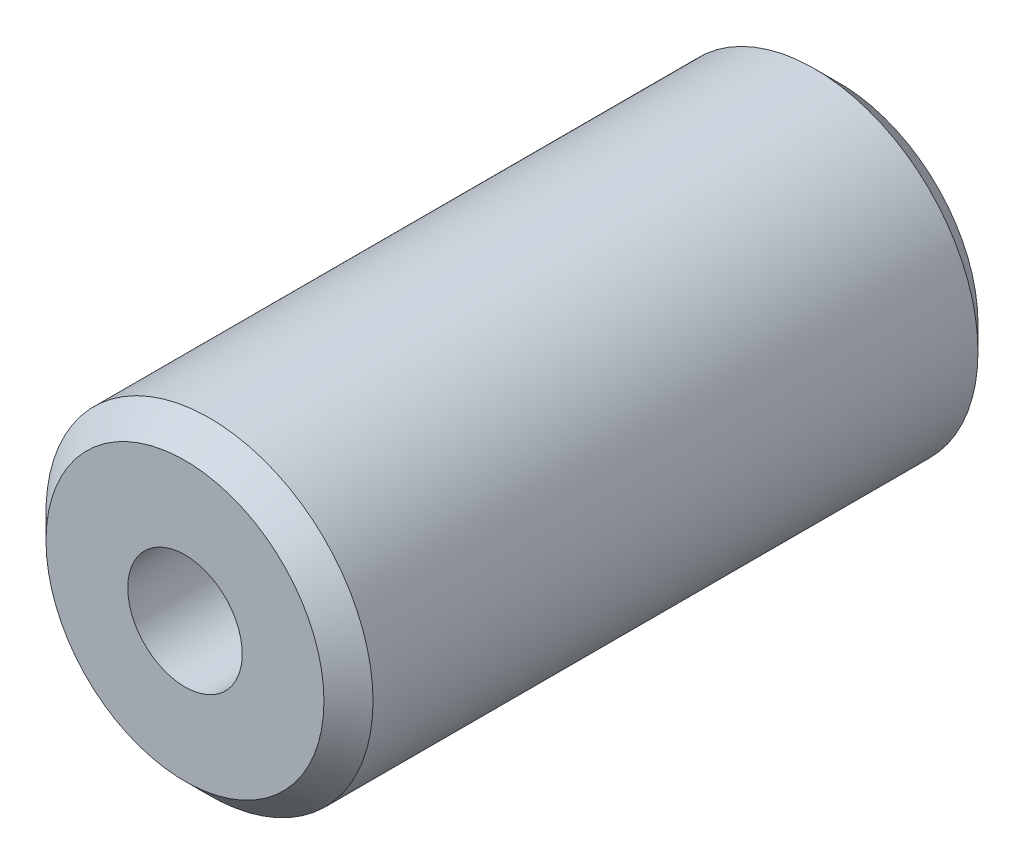
SolidWorks part; units mm, degrees
ref_plane "Front Plane" through (0, 0, 0) normal (0, 0, 1) x (1, 0, 0)
ref_plane "Top Plane" through (0, 0, 0) normal (0, 1, 0) x (1, 0, 0)
ref_plane "Right Plane" through (0, 0, 0) normal (1, 0, 0) x (0, 0, -1)
sketch "Sketch1" plane through (0, 0, 0) normal (0, 0, 1) x (1, 0, 0)
  circle A0 centre (0, 0) radius 10
  circle A1 centre (0, 0) radius 3.5
  dimension "D1" = 20
  dimension "D2" = 7
extrude "Boss-Extrude1" add sketch "Sketch1" along normal blind 40
chamfer "Chamfer1" distance 1.5 angle 45 2 edges at (10, 0, 40) (10, 0, 0)
sketch "Sketch2" plane through (0, 0, 0) normal (0, 0, -1) x (-1, 0, 0)
  circle A0 centre (0, 0) radius 6
  dimension "D1" = 12
extrude "Cut-Extrude1" cut sketch "Sketch2" against normal blind 25
sketch "Sketch3" plane through (0, 0, 0) normal (0, 1, 0) x (1, 0, 0)
  line L0 (-8.5, -40) -> (8.5, -40) construction
  circle A0 centre (0, -10) radius 2.5
  circle A1 centre (0, -30) radius 2.5
  dimension "D1" = 5
  dimension "D2" = 5
  dimension "D3" = 10
  dimension "D4" = 10
extrude "Cut-Extrude2" cut sketch "Sketch3" against normal blind 20
